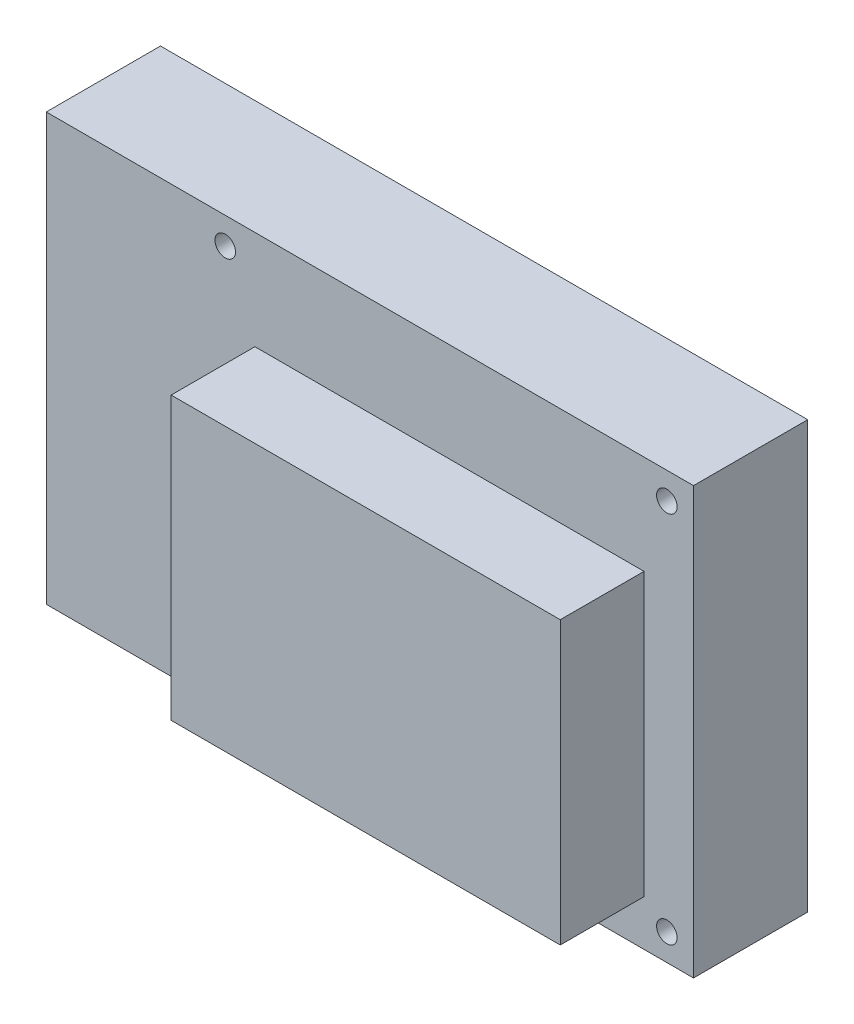
SolidWorks part; units mm, degrees
ref_plane "前视基准面" through (0, 0, 0) normal (0, 0, 1) x (1, 0, 0)
ref_plane "上视基准面" through (0, 0, 0) normal (0, 1, 0) x (1, 0, 0)
ref_plane "右视基准面" through (0, 0, 0) normal (1, 0, 0) x (0, 0, -1)
sketch "草图1" plane through (0, 0, 0) normal (0, 0, 1) x (1, 0, 0)
  line L1 (0, 0) -> (-85, 0)
  line L2 (0, 0) -> (0, 56)
  line L3 (0, 56) -> (-85, 56)
  line L4 (-85, 0) -> (-85, 56)
  circle A0 centre (-3.5, 52.5) radius 1.35
  circle A1 centre (-3.5, 3.5) radius 1.35
  circle A2 centre (-61.5, 3.5) radius 1.35
  circle A3 centre (-61.5, 52.5) radius 1.35
  dimension "D4" = 2.7
  dimension "D5" = 2.7
  dimension "D11" = 2.7
  dimension "D14" = 2.7
  dimension "D1" = 85
  dimension "D2" = 56
  dimension "D3" = 49
  dimension "D6" = 3.5
  dimension "D7" = 3.5
  dimension "D8" = 3.5
  dimension "D9" = 58
  dimension "D10" = 0
  dimension "D12" = 58
  dimension "D13" = 49
extrude "凸台-拉伸1" add sketch "草图1" along normal blind 15
sketch "草图2" plane through (0, 0, 15) normal (0, 0, 1) x (1, 0, 0)
  line L0 (0, 0) -> (0, 56) construction
  line L1 (-57.6, 43) -> (-6.5, 43)
  line L2 (-57.6, 43) -> (-57.6, 6)
  line L3 (-57.6, 6) -> (-6.5, 6)
  line L4 (-6.5, 43) -> (-6.5, 6)
  line L5 (-85, 0) -> (0, 0) construction
  dimension "D1" = 37
  dimension "D2" = 51.1
  dimension "D3" = 6.5
  dimension "D4" = 6
extrude "凸台-拉伸2" add sketch "草图2" along normal blind 11
